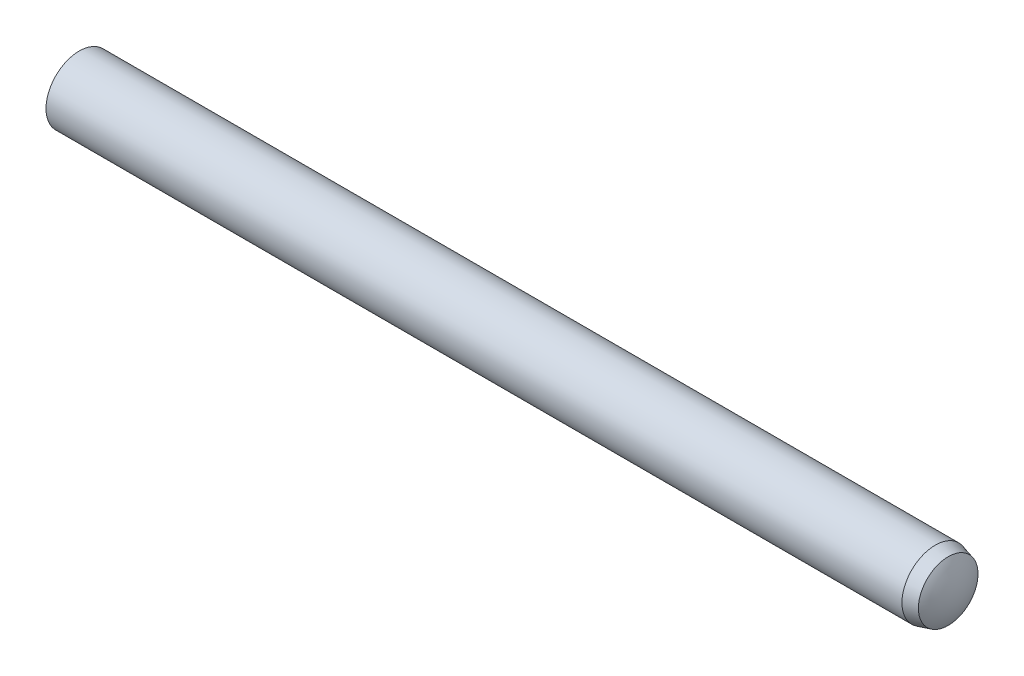
SolidWorks part; units mm, degrees
ref_plane "Front Plane" through (0, 0, 0) normal (0, 0, 1) x (1, 0, 0)
ref_plane "Top Plane" through (0, 0, 0) normal (0, 1, 0) x (1, 0, 0)
ref_plane "Right Plane" through (0, 0, 0) normal (1, 0, 0) x (0, 0, -1)
sketch "Sketch1" plane through (0, 0, 0) normal (0, 0, 1) x (1, 0, 0)
  line L0 (-20, 0) -> (20, 0) construction
  line L1 (20, 1.5) -> (20, -1.5) construction
  line L2 (-20, 1.5) -> (-20, -1.5) construction
  line L3 (19.025, 1.5) -> (19.025, -1.5) construction
  line L4 (-19.55, 1.5) -> (-19.55, -1.5) construction
  line L5 (-20, 0) -> (-19.55, 0) construction
  line L6 (20, 0) -> (19.025, 0) construction
  line L7 (19.61, 1.5) -> (19.61, -1.5) construction
  dimension "D1" = 0.975
  dimension "Dia" = 3
  dimension "D2" = 0.45
  dimension "Length" = 40
  dimension "D3" = 0.585
sketch "Sketch2" plane through (0, 0, 0) normal (1, 0, 0) x (0, 0, -1)
  circle A0 centre (0, 0) radius 1.5
extrude "Extrude1" add sketch "Sketch2" against normal up to vertex (20 mm away) and the other way up to vertex (20 mm away) up to point (-20, 0, 0) other way up to point (20, 0, 0)
sketch "Sketch5" plane through (0, 0, 0) normal (0, 0, 1) x (1, 0, 0)
  line L0 (19.025, 1.5) -> (19.025, 2)
  line L1 (19.025, 2) -> (20.5, 2)
  line L2 (20.5, 2) -> (20.5, 0)
  line L3 (20, 0) -> (20.5, 0)
  line L5 (-19.55, 1.5) -> (-19.55, 2)
  line L6 (-19.55, 2) -> (-20.5, 2)
  line L7 (-20.5, 2) -> (-20.5, 0)
  line L8 (19.025, 1.5) -> (19.61, 1.3432)
  line L10 (-20, 0) -> (-20.5, 0)
  line L11 (-20, 1.5) -> (-20, -1.5) construction
  line L13 (19.025, 1.5) -> (19.025, -1.5) construction
  line L15 (-20, 0) -> (20, 0) construction
  line L16 (19.61, 1.5) -> (19.61, -1.5) construction
  line L17 (20, 1.5) -> (20, -1.5) construction
  arc A0 (19.61, 1.3432) -> (20, 0) centre (17.4918, 0) cw
  arc A1 (-19.55, 1.5) -> (-20, 0) centre (-17.275, 0) ccw
  dimension "D1" = 15
  dimension "D2" = 0.5
revolve "Cut-Revolve1" cut sketch "Sketch5" angle 360 about L0
equation "\"D1@Sketch1\" = \"Dia@Sketch1\"*.325"
equation "\"D2@Sketch1\" = \"Dia@Sketch1\"*.15"
equation "\"D3@Sketch1\" = \"D1@Sketch1\"*.6"
